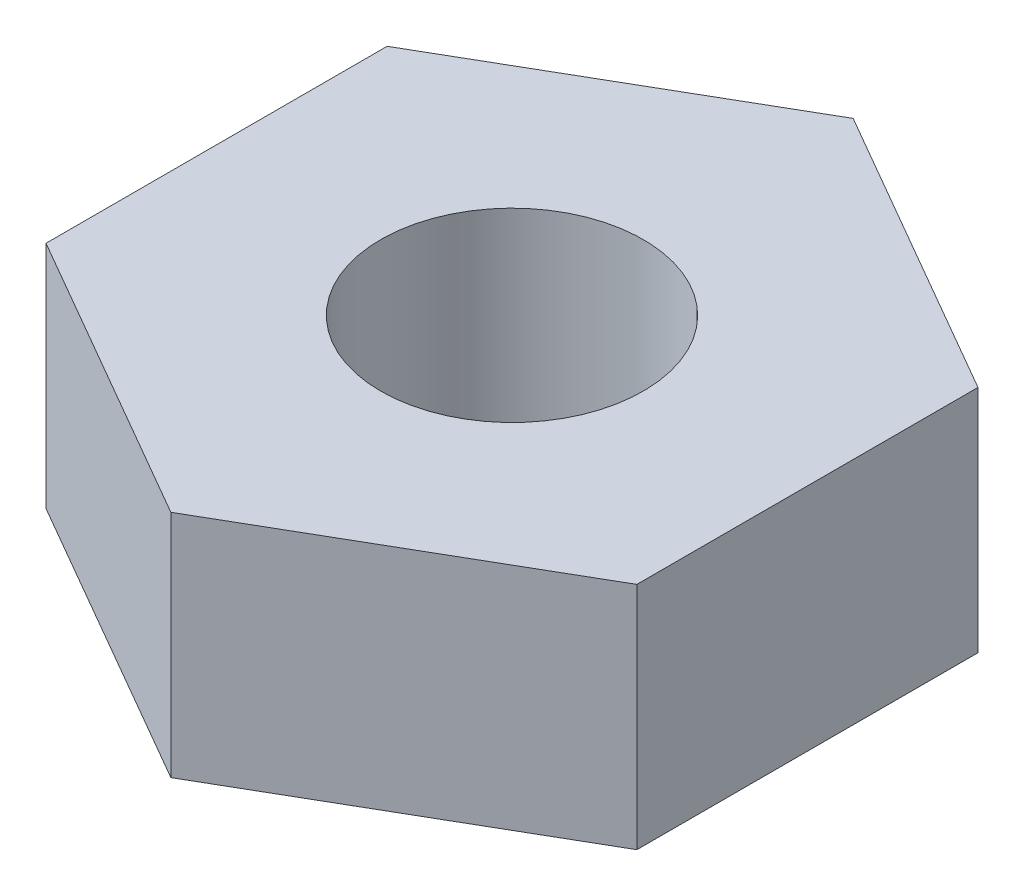
SolidWorks part; units mm, degrees
ref_plane "Front Plane" through (0, 0, 0) normal (0, 0, 1) x (1, 0, 0)
ref_plane "Top Plane" through (0, 0, 0) normal (0, 1, 0) x (1, 0, 0)
ref_plane "Right Plane" through (0, 0, 0) normal (1, 0, 0) x (0, 0, -1)
sketch "Sketch1" plane through (0, 0, 0) normal (0, 1, 0) x (1, 0, 0)
  line L1 (0, 2.5981) -> (-2.25, 1.299)
  line L2 (-2.25, 1.299) -> (-2.25, -1.299)
  line L3 (-2.25, -1.299) -> (0, -2.5981)
  line L4 (0, -2.5981) -> (2.25, -1.299)
  line L5 (2.25, -1.299) -> (2.25, 1.299)
  line L6 (2.25, 1.299) -> (0, 2.5981)
  circle A0 centre (0, 0) radius 1
  circle A1 centre (0, 0) radius 2.25 construction
  dimension "D1" = 2
  dimension "D2" = 4.5
extrude "Boss-Extrude1" add sketch "Sketch1" along normal blind 1.75
